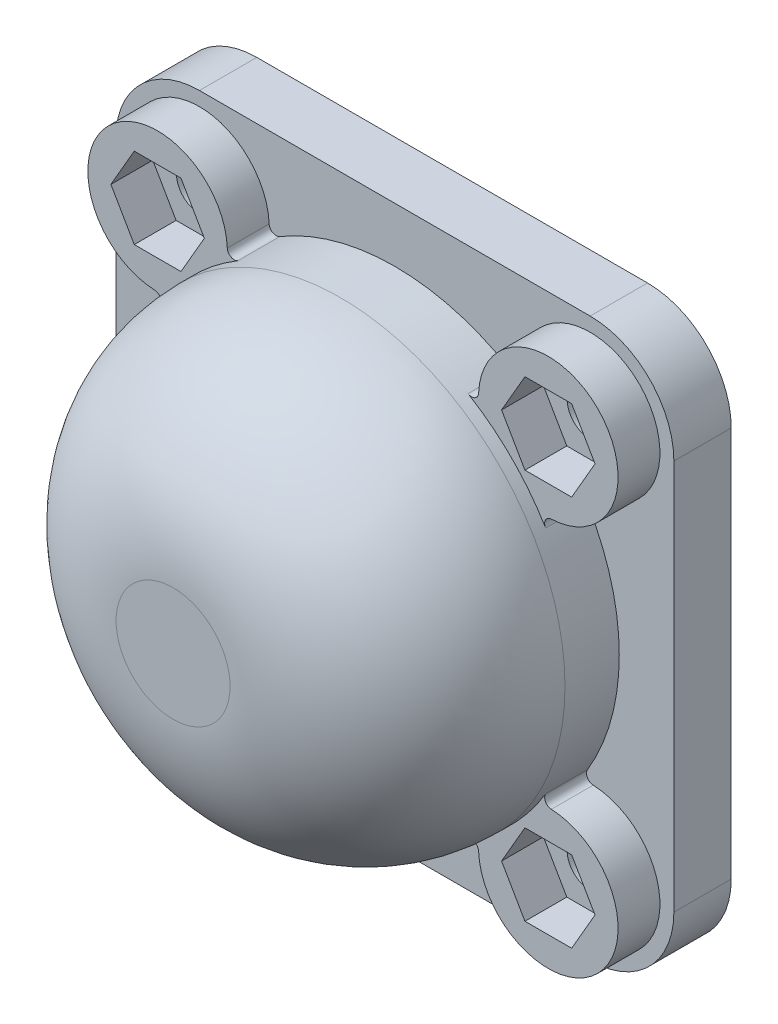
SolidWorks part; units mm, degrees
ref_plane "Front Plane" through (0, 0, 0) normal (0, 0, 1) x (1, 0, 0)
ref_plane "Top Plane" through (0, 0, 0) normal (0, 1, 0) x (1, 0, 0)
ref_plane "Right Plane" through (0, 0, 0) normal (1, 0, 0) x (0, 0, -1)
sketch "Sketch1" plane through (0, 0, 0) normal (0, 0, 1) x (1, 0, 0)
  line L0 (-20, 14) -> (-20, -14)
  line L2 (-14, -20) -> (14, -20)
  line L4 (20, -14) -> (20, 14)
  line L6 (14, 20) -> (-14, 20)
  circle A3 centre (-14, 14) radius 1.65
  circle A4 centre (-14, -14) radius 1.65
  circle A5 centre (14, -14) radius 1.65
  circle A6 centre (14, 14) radius 1.65
  arc A9 (-14, 20) -> (-20, 14) centre (-14, 14) ccw
  arc A10 (20, 14) -> (14, 20) centre (14, 14) ccw
  arc A11 (-20, -14) -> (-14, -20) centre (-14, -14) ccw
  arc A12 (14, -20) -> (20, -14) centre (14, -14) ccw
extrude "Boss-Extrude1" add sketch "Sketch1" along normal blind 20
sketch "Sketch3" plane through (0, 0, 0) normal (1, 0, 0) x (0, 0, -1)
  line L0 (0, 0) -> (0, 10)
  line L1 (-22.5, 0) -> (2.5, 0) construction
  line L4 (-8, 16.0864) -> (-4.1101, 16.0864)
  line L5 (0, 0) -> (0, 10)
  line L7 (0, 10) -> (-0.7955, 10)
  line L8 (-17, 0) -> (0, 0)
  line L10 (0, 10) -> (0, 0)
  line L11 (-17, 0) -> (-17, 4.0864)
  line L12 (-4.1101, 16.0864) -> (-4.1101, 25.8)
  line L13 (-20, 4.0864) -> (-20, 25.8)
  line L16 (-20, 25.8) -> (-4.1101, 25.8)
  arc A0 (-4.1101, 12.2024) -> (-1.1428, 10.1402) centre (-9, 2) cw
  arc A1 (-17, 4.0864) -> (-4.1101, 12.2024) centre (-8, 4.0864) cw
  arc A2 (-0.7955, 10) -> (-1.1428, 10.1402) centre (-0.7955, 10.5) cw
  arc A3 (-8, 16.0864) -> (-20, 4.0864) centre (-8, 4.0864) ccw
revolve "Cut-Revolve3" cut sketch "Sketch3" angle 360 about L1
sketch "Sketch4" plane through (0, 0, 4.1101) normal (0, 0, 1) x (1, 0, 0)
  line L1 (-10.6514, 14) -> (-12.3257, 16.9)
  line L2 (-12.3257, 16.9) -> (-15.6743, 16.9)
  line L3 (-15.6743, 16.9) -> (-17.3486, 14)
  line L4 (-17.3486, 14) -> (-15.6743, 11.1)
  line L5 (-15.6743, 11.1) -> (-12.3257, 11.1)
  line L6 (-12.3257, 11.1) -> (-10.6514, 14)
  line L7 (17.3486, 14) -> (15.6743, 16.9)
  line L8 (15.6743, 16.9) -> (12.3257, 16.9)
  line L9 (12.3257, 16.9) -> (10.6514, 14)
  line L10 (10.6514, 14) -> (12.3257, 11.1)
  line L11 (12.3257, 11.1) -> (15.6743, 11.1)
  line L12 (15.6743, 11.1) -> (17.3486, 14)
  line L13 (17.3486, -14) -> (15.6743, -11.1)
  line L14 (15.6743, -11.1) -> (12.3257, -11.1)
  line L15 (12.3257, -11.1) -> (10.6514, -14)
  line L16 (10.6514, -14) -> (12.3257, -16.9)
  line L17 (12.3257, -16.9) -> (15.6743, -16.9)
  line L18 (15.6743, -16.9) -> (17.3486, -14)
  line L19 (-10.6514, -14) -> (-12.3257, -11.1)
  line L20 (-12.3257, -11.1) -> (-15.6743, -11.1)
  line L21 (-15.6743, -11.1) -> (-17.3486, -14)
  line L22 (-17.3486, -14) -> (-15.6743, -16.9)
  line L23 (-15.6743, -16.9) -> (-12.3257, -16.9)
  line L24 (-12.3257, -16.9) -> (-10.6514, -14)
  arc A0 (-9.0048, 14.218) -> (-14.218, 9.0048) centre (-14, 14) ccw
  arc A1 (14.218, 9.0048) -> (9.0048, 14.218) centre (14, 14) ccw
  arc A2 (9.0048, -14.218) -> (14.218, -9.0048) centre (14, -14) ccw
  arc A3 (-14.218, -9.0048) -> (-9.0048, -14.218) centre (-14, -14) ccw
  arc A12 (-14.218, -9.0048) -> (-13.8105, -8.2488) centre (-14.2398, -8.5052) ccw
  arc A13 (9.0048, -14.218) -> (8.2488, -13.8105) centre (8.5052, -14.2398) ccw
  arc A14 (14.218, -9.0048) -> (13.8105, -8.2488) centre (14.2398, -8.5052) cw
  arc A15 (9.0048, 14.218) -> (8.2488, 13.8105) centre (8.5052, 14.2398) cw
  arc A16 (14.218, 9.0048) -> (13.8105, 8.2488) centre (14.2398, 8.5052) ccw
  arc A17 (-14.218, 9.0048) -> (-13.8105, 8.2488) centre (-14.2398, 8.5052) cw
  arc A18 (-9.0048, 14.218) -> (-8.2488, 13.8105) centre (-8.5052, 14.2398) ccw
  arc A19 (-9.0048, -14.218) -> (-8.2488, -13.8105) centre (-8.5052, -14.2398) cw
  arc A20 (-8.2488, 13.8105) -> (-13.8105, 8.2488) centre (0, 0) ccw
  arc A21 (13.8105, 8.2488) -> (8.2488, 13.8105) centre (0, 0) ccw
  arc A22 (-13.8105, -8.2488) -> (-8.2488, -13.8105) centre (0, 0) ccw
  arc A23 (8.2488, -13.8105) -> (13.8105, -8.2488) centre (0, 0) ccw
  point P59 (0, 0)
  point P64 (0, 0)
  point P65 (0, 0)
extrude "Boss-Extrude2" add sketch "Sketch4" along normal blind 3
